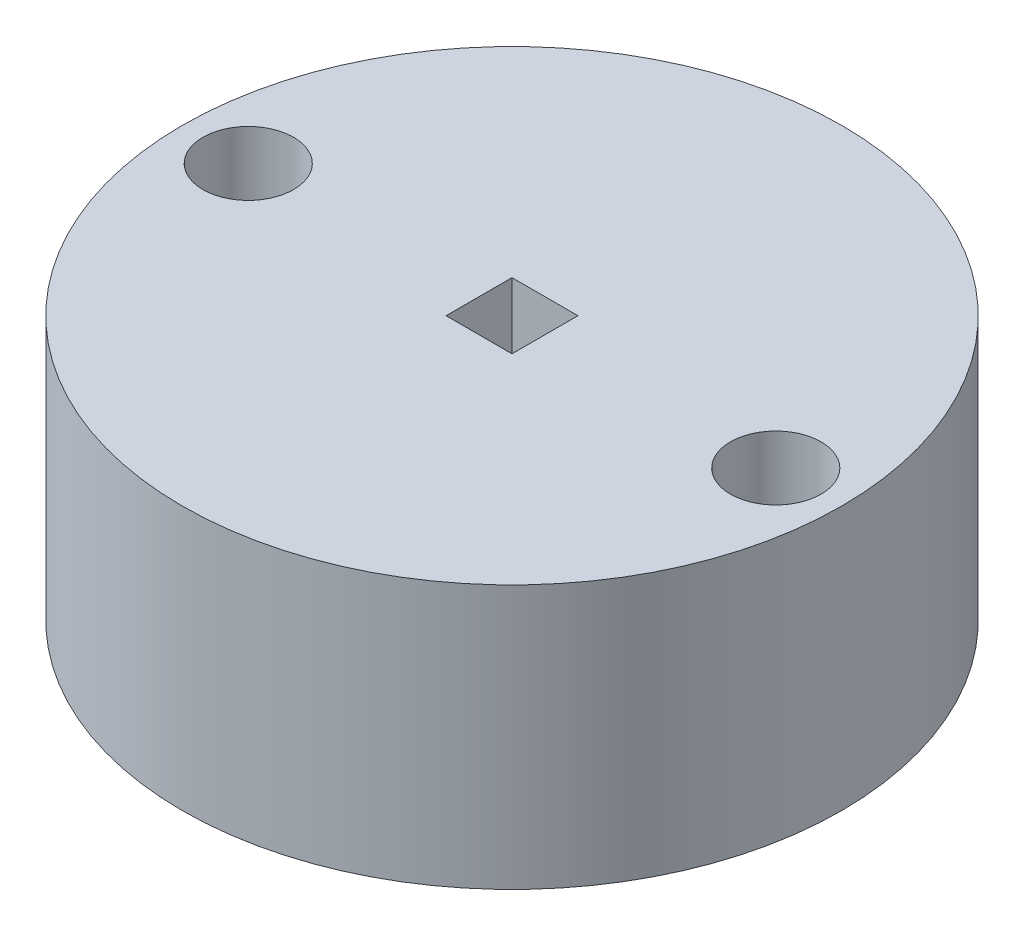
SolidWorks part; units mm, degrees
ref_plane "Front Plane" through (0, 0, 0) normal (0, 0, 1) x (1, 0, 0)
ref_plane "Top Plane" through (0, 0, 0) normal (0, 1, 0) x (1, 0, 0)
ref_plane "Right Plane" through (0, 0, 0) normal (1, 0, 0) x (0, 0, -1)
sketch "Sketch1" plane through (0, 0, 0) normal (0, 1, 0) x (1, 0, 0)
  line L1 (-1.5875, -1.5875) -> (1.5875, -1.5875)
  line L2 (-1.5875, -1.5875) -> (-1.5875, 1.5875)
  line L3 (-1.5875, 1.5875) -> (1.5875, 1.5875)
  line L4 (1.5875, -1.5875) -> (1.5875, 1.5875)
  line L5 (-1.5875, -1.5875) -> (1.5875, 1.5875) construction
  line L6 (-1.5875, 1.5875) -> (1.5875, -1.5875) construction
  circle A1 centre (12.7, 0) radius 2.1828
  circle A2 centre (-12.7, 0) radius 2.1828
  circle A3 centre (0, 0) radius 15.875
  dimension "D3" = 4.3656
  dimension "D4" = 3.175
  dimension "D5" = 4.3656
  dimension "D6" = 31.75
  dimension "D1" = 12.7
  dimension "D2" = 12.7
  dimension "D7" = 3.175
extrude "Boss-Extrude1" add sketch "Sketch1" along normal blind 12.7
